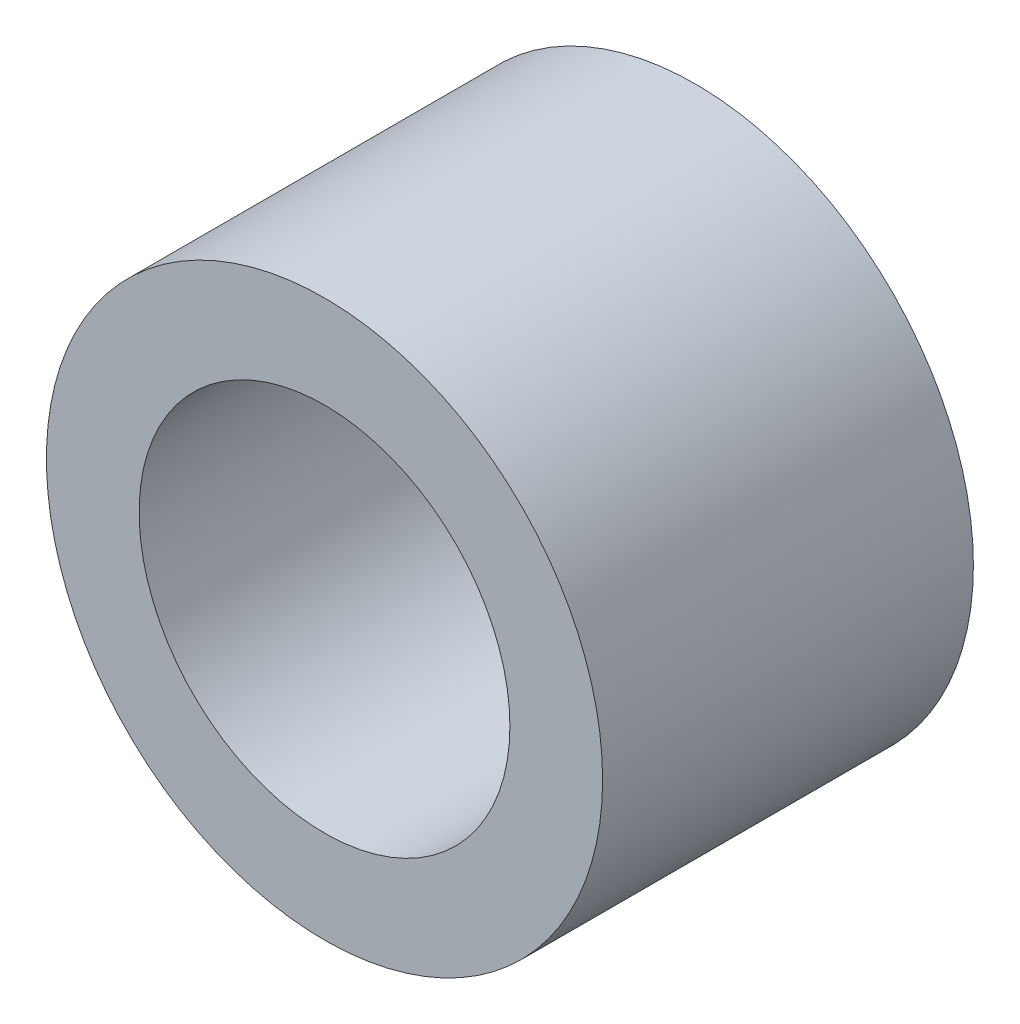
SolidWorks part; units mm, degrees
material "Delrin 2700 NC010, Low Viscosity Acetal Copolymer (SS)"
ref_plane "Front Plane" through (0, 0, 0) normal (0, 0, 1) x (1, 0, 0)
ref_plane "Top Plane" through (0, 0, 0) normal (0, 1, 0) x (1, 0, 0)
ref_plane "Right Plane" through (0, 0, 0) normal (1, 0, 0) x (0, 0, -1)
sketch "Sketch1" plane through (0, 0, 0) normal (0, 0, 1) x (1, 0, 0)
  circle A0 centre (0, 0) radius 4.7625
  circle A1 centre (0, 0) radius 3.175
  dimension "D1" = 9.525
  dimension "D2" = 6.35
extrude "Boss-Extrude1" add sketch "Sketch1" along normal blind 6.35
